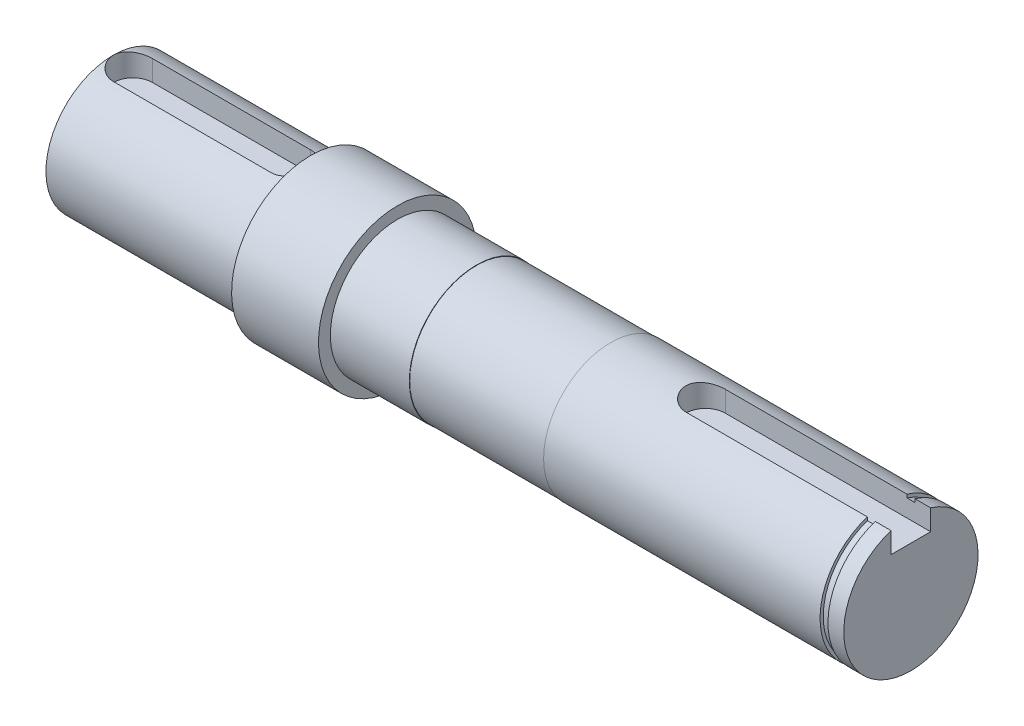
SolidWorks part; units mm, degrees
material "AISI 1020"
ref_plane "Plano frontal" through (0, 0, 0) normal (0, 0, 1) x (1, 0, 0)
ref_plane "Plano superior" through (0, 0, 0) normal (0, 1, 0) x (1, 0, 0)
ref_plane "Plano direito" through (0, 0, 0) normal (1, 0, 0) x (0, 0, -1)
sketch "Esboço1" plane through (0, 0, 0) normal (0, 0, 1) x (1, 0, 0)
  line L0 (0, 0) -> (0, 8.5)
  line L1 (25, 10) -> (36, 10)
  line L2 (36, 10) -> (36, 8.5)
  line L3 (36, 8.5) -> (101, 8.5)
  line L4 (25, 10) -> (25, 8.5)
  line L5 (25, 8.5) -> (0, 8.5)
  line L6 (101, 8.5) -> (101, 0)
  line L7 (101, 0) -> (0, 0) construction
  line L8 (0, 0) -> (101, 0)
  dimension "D1" = 20
  dimension "D2" = 17
  dimension "D3" = 11
  dimension "D4" = 25
  dimension "D5" = 65
revolve "Revolução1" add sketch "Esboço1" angle 360 about L7
sketch "Esboço2" plane through (0, 0, 0) normal (0, 0, 1) x (1, 0, 0)
  line L0 (0, 0) -> (55.4211, 0) construction
  line L2 (98, 8.5) -> (99, 8.5)
  line L3 (98, 8.5) -> (98, 8.1)
  line L4 (98, 8.1) -> (99, 8.1)
  line L5 (99, 8.5) -> (99, 8.1)
  line L7 (101, -8.5) -> (101, 8.5) construction
  dimension "D1" = 16.2
  dimension "D2" = 1
  dimension "D3" = 2
revolve "Corte-Revolução1" cut sketch "Esboço2" angle 360 about L0
ref_plane "Plano1" through (0, 8.5, 0) normal (0, 1, 0) x (1, 0, 0)
sketch "Esboço3" plane through (0, 8.5, 0) normal (0, 1, 0) x (1, 0, 0)
  line L0 (75, 0) -> (105, 0) construction
  line L2 (75, -2.5) -> (105, -2.5)
  line L3 (75, 2.5) -> (105, 2.5)
  line L5 (101, -8.5) -> (101, 8.5) construction
  arc A0 (75, -2.5) -> (75, 2.5) centre (75, 0) cw
  arc A1 (105, -2.5) -> (105, 2.5) centre (105, 0) ccw
  dimension "D1" = 30
  dimension "D4" = 26
  dimension "D2" = 2.5
  dimension "D3" = 2.5
extrude "Corte-extrusão1" cut sketch "Esboço3" against normal blind 3 and the other way through all
ref_plane "Plano3" through (0, 8.5, 0) normal (0, 1, 0) x (-1, 0, 0)
sketch "Esboço5" plane through (0, 8.5, 0) normal (0, 1, 0) x (-1, 0, 0)
  line L0 (-2.51, 0) -> (-22.51, 0) construction
  line L1 (0, -10) -> (0, 10) construction
  line L2 (-2.51, 2.5) -> (-22.51, 2.5)
  line L3 (-2.51, -2.5) -> (-22.51, -2.5)
  arc A0 (-2.51, 2.5) -> (-2.51, -2.5) centre (-2.51, 0) cw
  arc A1 (-22.51, 2.5) -> (-22.51, -2.5) centre (-22.51, 0) ccw
  dimension "D1" = 20
  dimension "D2" = 2.51
  dimension "D3" = 2.5
  dimension "D4" = 2.5
extrude "Corte-extrusão7" cut sketch "Esboço5" against normal blind 3
sketch "Esboço6" plane through (0, 0, 0) normal (0, 1, 0) x (1, 0, 0)
  line L0 (98, 8.5) -> (36, 8.5) construction
  line L1 (46, 8.5) -> (63, 8.5)
  line L2 (46, 8.5) -> (46, 8.45)
  line L3 (46, 8.45) -> (63, 8.45)
  line L4 (63, 8.5) -> (63, 8.45)
  line L5 (48.8761, 0) -> (58.3277, 0) construction
  line L6 (46, -11.3) -> (46, 11.3) construction
  line L7 (63, 16.5) -> (63, -16.5) construction
  dimension "D1" = 16.9
revolve "Corte-Revolução2" cut sketch "Esboço6" angle 360 about L5
